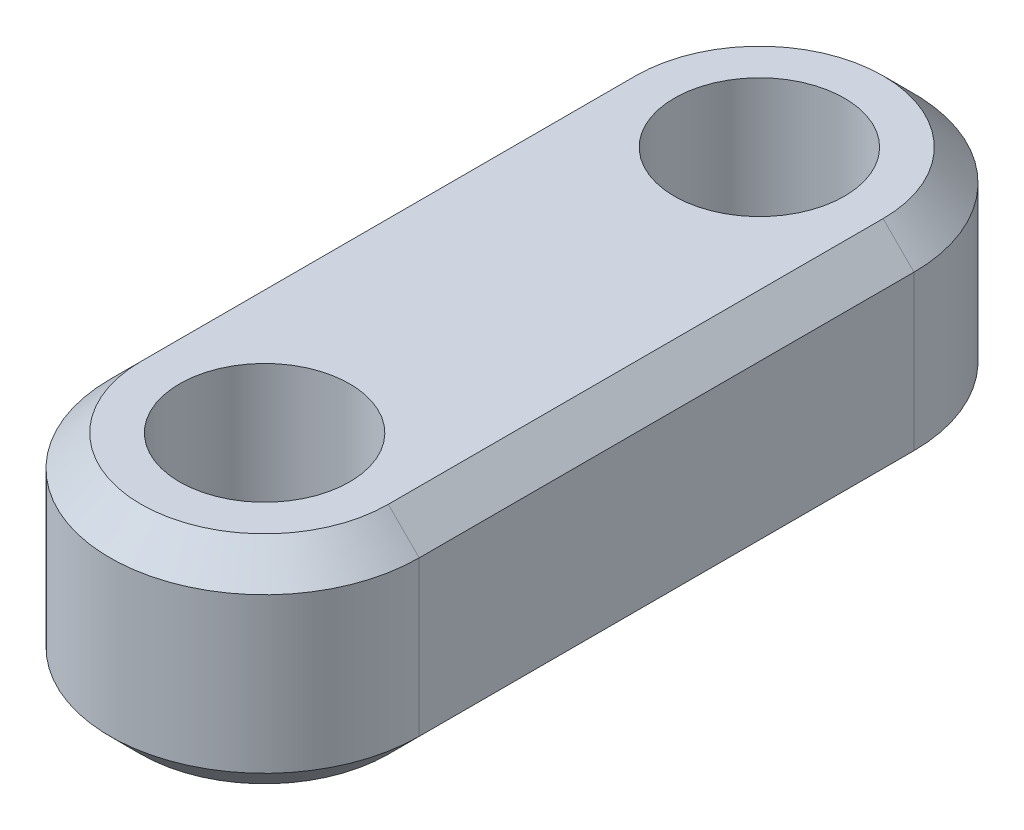
SolidWorks part; units mm, degrees
ref_plane "前视基准面" through (0, 0, 0) normal (0, 0, 1) x (1, 0, 0)
ref_plane "上视基准面" through (0, 0, 0) normal (0, 1, 0) x (1, 0, 0)
ref_plane "右视基准面" through (0, 0, 0) normal (1, 0, 0) x (0, 0, -1)
other "Configuration Table"
sketch "草图1" plane through (0, 0, 0) normal (0, 1, 0) x (1, 0, 0)
  line L0 (0, 0) -> (0, -16) construction
  line L1 (-5, -16) -> (-5, 0)
  line L2 (5, -16) -> (5, 0)
  arc A0 (5, 0) -> (-5, 0) centre (0, 0) ccw
  arc A1 (-5, -16) -> (5, -16) centre (0, -16) ccw
  circle A2 centre (0, 0) radius 2.75
  circle A3 centre (0, -16) radius 2.75
  dimension "D1" = 10
  dimension "D3" = 10
  dimension "D4" = 5.5
  dimension "D5" = 5.5
  dimension "D2" = 16
extrude "凸台-拉伸1" add sketch "草图1" along normal blind 7
chamfer "倒角1" distance 1 angle 45 8 edges at (0, 0, -5) (-5, 0, 8) (0, 0, 21) (5, 0, 8) (0, 7, 21) (-5, 7, 8) (0, 7, -5) (5, 7, 8)
